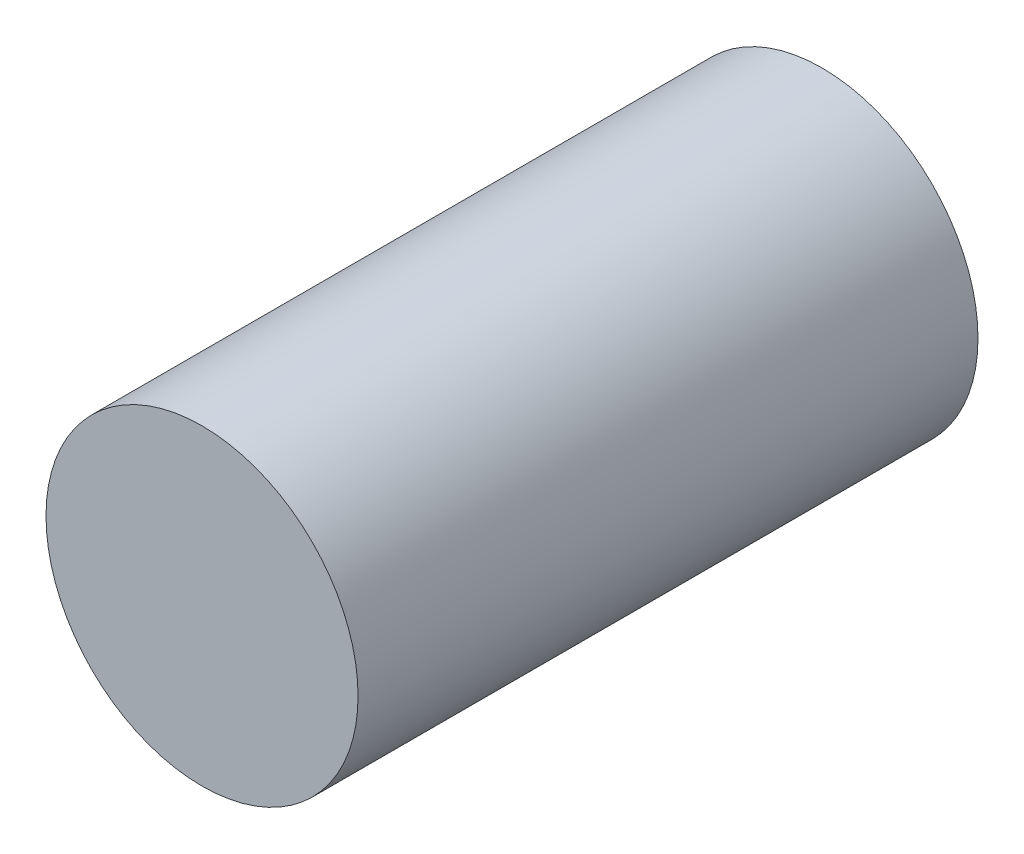
SolidWorks part; units mm, degrees
ref_plane "Front Plane" through (0, 0, 0) normal (0, 0, 1) x (1, 0, 0)
ref_plane "Top Plane" through (0, 0, 0) normal (0, 1, 0) x (1, 0, 0)
ref_plane "Right Plane" through (0, 0, 0) normal (1, 0, 0) x (0, 0, -1)
sketch "Sketch1" plane through (0, 0, 0) normal (0, 0, 1) x (1, 0, 0)
  circle A0 centre (0, 0) radius 37.25
  dimension "D1" = 74.5
extrude "Boss-Extrude1" add sketch "Sketch1" along normal blind 148
